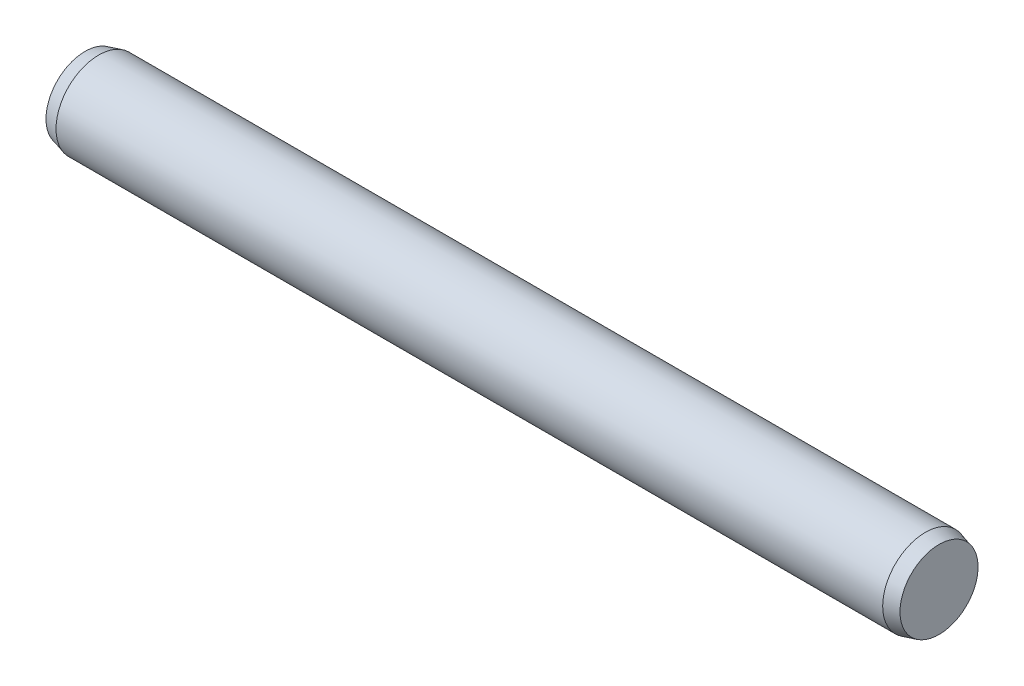
SolidWorks part; units mm, degrees
ref_plane "Plane1" through (0, 0, 0) normal (0, 0, 1) x (1, 0, 0)
ref_plane "Plane2" through (0, 0, 0) normal (0, 1, 0) x (1, 0, 0)
ref_plane "Plane3" through (0, 0, 0) normal (1, 0, 0) x (0, 0, -1)
sketch "Sketch1" plane through (0, 0, 0) normal (0, 0, 1) x (1, 0, 0)
  line L1 (-6.35, 0) -> (107.95, 0) construction
  line L2 (0, 0) -> (50, 0)
  line L3 (50, 0) -> (50, 2.2856)
  line L4 (50, 2.2856) -> (49.2, 2.5)
  line L5 (49.2, 2.5) -> (0.8, 2.5)
  line L6 (0, 2.2856) -> (0, 0)
  line L7 (0, 2.2856) -> (0.8, 2.5)
  dimension "Chamfer_len" = 0.8
  dimension "D3" = 15
  dimension "Diameter" = 5
  dimension "D1" = 0.8
  dimension "D2" = 15
  dimension "Length" = 50
revolve "Base-Revolve" add sketch "Sketch1" angle 360 about L1
equation "\"D3@Sketch1\" = 15.0"
equation "\"D1@Sketch1\" = \"Chamfer_len@Sketch1\""
equation "\"D2@Sketch1\" = \"D3@Sketch1\""
